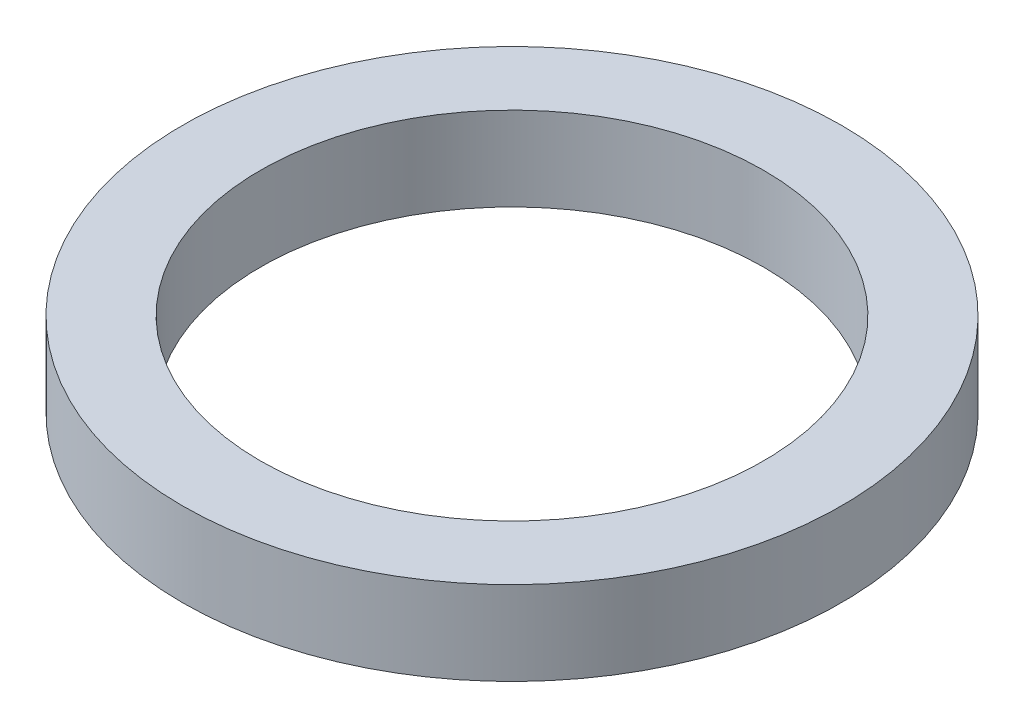
SolidWorks part; units mm, degrees
ref_plane "Спереди" through (0, 0, 0) normal (0, 0, 1) x (1, 0, 0)
ref_plane "Сверху" through (0, 0, 0) normal (0, 1, 0) x (1, 0, 0)
ref_plane "Справа" through (0, 0, 0) normal (1, 0, 0) x (0, 0, -1)
sketch "Эскиз1" plane through (0, 0, 0) normal (0, 1, 0) x (1, 0, 0)
  circle A0 centre (0, 0) radius 2.1
  circle A1 centre (0, 0) radius 2.75
  dimension "D1" = 5.5
  dimension "D2" = 4.2
extrude "Бобышка-Вытянуть1" add sketch "Эскиз1" along normal blind 0.7
